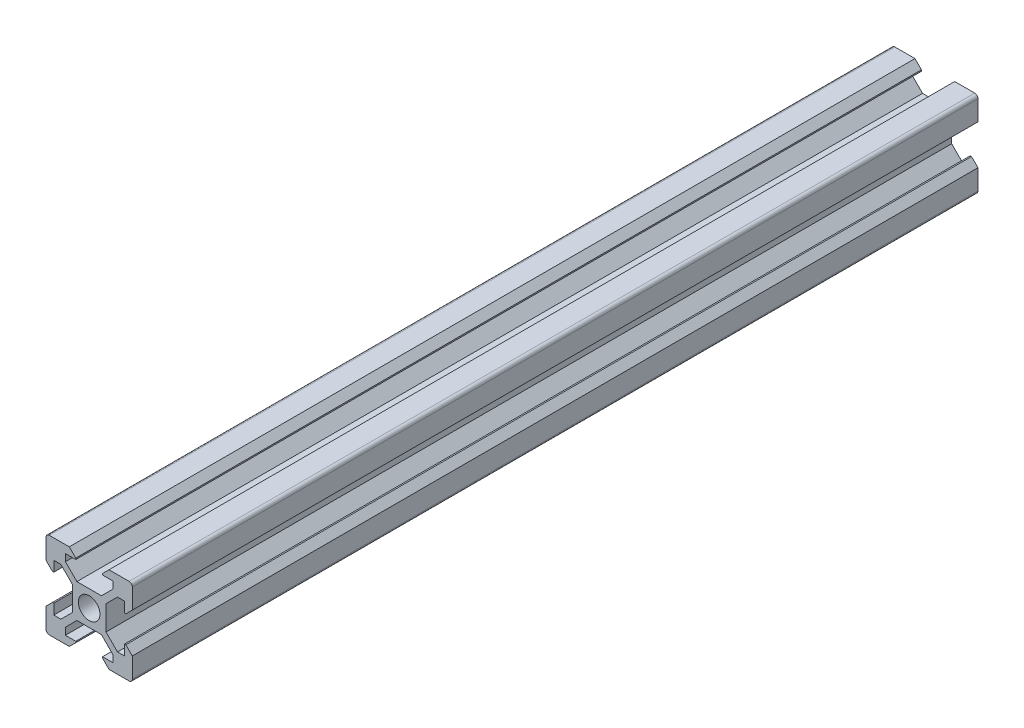
SolidWorks part; units mm, degrees
other "Markup1"
sketch "Sketch1" plane through (10, 10, 480) normal (0.5774, 0.5773, 0.5774) x (0.7071, 0, -0.7071)
ref_plane "Alzado" through (0, 0, 0) normal (0, 0, 1) x (1, 0, 0)
ref_plane "Planta" through (0, 0, 0) normal (0, 1, 0) x (1, 0, 0)
ref_plane "Vista lateral" through (0, 0, 0) normal (1, 0, 0) x (0, 0, -1)
sketch "Croquis1" plane through (0, 0, 0) normal (0, 0, 1) x (1, 0, 0)
  line L0 (-4.6, 10) -> (-3.1, 8.5)
  line L3 (-4.6, 10) -> (-9.25, 10)
  line L5 (-3.1, 8.5) -> (-3.1, 8.2)
  line L6 (-3.1, 8.2) -> (-5.5, 8.2)
  line L7 (-5.5, 8.2) -> (-5.5, 6.5607)
  line L8 (-5.5, 6.5607) -> (-2.84, 3.9007)
  line L9 (-2.84, 3.9007) -> (0, 3.9007)
  line L10 (0, 0) -> (-15.3499, 15.3499) construction
  line L11 (-3.9007, 2.84) -> (-3.9007, 0)
  line L12 (-6.5607, 5.5) -> (-3.9007, 2.84)
  line L13 (-8.2, 5.5) -> (-6.5607, 5.5)
  line L14 (-8.2, 3.1) -> (-8.2, 5.5)
  line L15 (-8.5, 3.1) -> (-8.2, 3.1)
  line L16 (-10, 4.6) -> (-10, 9.25)
  line L17 (-10, 4.6) -> (-8.5, 3.1)
  line L18 (10, 4.6) -> (8.5, 3.1)
  line L19 (10, 4.6) -> (10, 9.25)
  line L20 (8.5, 3.1) -> (8.2, 3.1)
  line L21 (8.2, 3.1) -> (8.2, 5.5)
  line L22 (8.2, 5.5) -> (6.5607, 5.5)
  line L23 (6.5607, 5.5) -> (3.9007, 2.84)
  line L24 (3.9007, 2.84) -> (3.9007, 0)
  line L25 (5.5, 6.5607) -> (2.84, 3.9007)
  line L26 (5.5, 8.2) -> (5.5, 6.5607)
  line L27 (3.1, 8.2) -> (5.5, 8.2)
  line L28 (3.1, 8.5) -> (3.1, 8.2)
  line L29 (4.6, 10) -> (9.25, 10)
  line L30 (4.6, 10) -> (3.1, 8.5)
  line L31 (2.84, 3.9007) -> (0, 3.9007)
  line L32 (4.6, -10) -> (3.1, -8.5)
  line L33 (4.6, -10) -> (9.25, -10)
  line L34 (3.1, -8.5) -> (3.1, -8.2)
  line L35 (3.1, -8.2) -> (5.5, -8.2)
  line L36 (5.5, -8.2) -> (5.5, -6.5607)
  line L37 (5.5, -6.5607) -> (2.84, -3.9007)
  line L38 (2.84, -3.9007) -> (0, -3.9007)
  line L39 (6.5607, -5.5) -> (3.9007, -2.84)
  line L40 (8.2, -5.5) -> (6.5607, -5.5)
  line L41 (8.2, -3.1) -> (8.2, -5.5)
  line L42 (8.5, -3.1) -> (8.2, -3.1)
  line L43 (10, -4.6) -> (10, -9.25)
  line L44 (10, -4.6) -> (8.5, -3.1)
  line L45 (3.9007, -2.84) -> (3.9007, 0)
  line L46 (-10, -4.6) -> (-8.5, -3.1)
  line L47 (-10, -4.6) -> (-10, -9.25)
  line L48 (-8.5, -3.1) -> (-8.2, -3.1)
  line L49 (-8.2, -3.1) -> (-8.2, -5.5)
  line L50 (-8.2, -5.5) -> (-6.5607, -5.5)
  line L51 (-6.5607, -5.5) -> (-3.9007, -2.84)
  line L52 (-3.9007, -2.84) -> (-3.9007, 0)
  line L53 (-5.5, -6.5607) -> (-2.84, -3.9007)
  line L54 (-5.5, -8.2) -> (-5.5, -6.5607)
  line L55 (-3.1, -8.2) -> (-5.5, -8.2)
  line L56 (-3.1, -8.5) -> (-3.1, -8.2)
  line L57 (-4.6, -10) -> (-9.25, -10)
  line L58 (-4.6, -10) -> (-3.1, -8.5)
  line L59 (-2.84, -3.9007) -> (0, -3.9007)
  circle A0 centre (0, 0) radius 2.5
  arc A1 (-9.25, 10) -> (-10, 9.25) centre (-9.25, 9.25) ccw
  arc A2 (10, 9.25) -> (9.25, 10) centre (9.25, 9.25) ccw
  arc A3 (9.25, -10) -> (10, -9.25) centre (9.25, -9.25) ccw
  arc A4 (-10, -9.25) -> (-9.25, -10) centre (-9.25, -9.25) ccw
  point P18 (-10, 10)
  point P37 (10, 10)
  point P55 (10, -10)
  point P73 (-10, -10)
  point P79 (0, 0)
  dimension "D1" = 5
  dimension "D5" = 0.75
  dimension "D2" = 10
  dimension "D3" = 10
  dimension "D4" = 4.6
  dimension "D6" = 5.5
  dimension "D7" = 135
  dimension "D8" = 0.75
  dimension "D9" = 225
  dimension "D10" = 2.84
  dimension "D11" = 1.8
  dimension "D12" = 3.1
  dimension "D13" = 4
extrude "Saliente-Extruir1" add sketch "Croquis1" along normal blind 195.95
